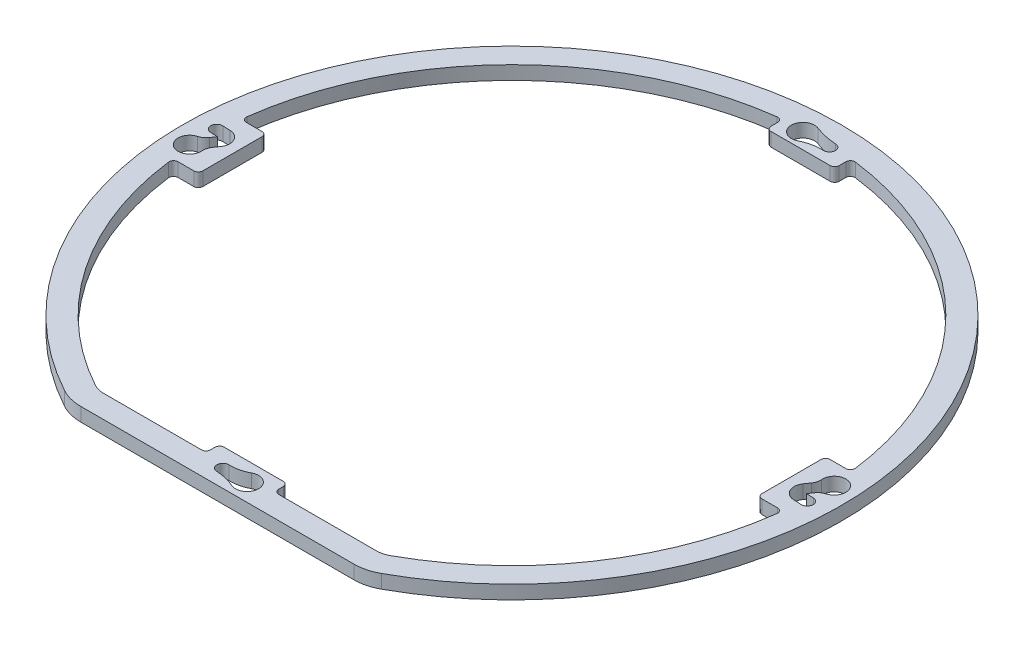
SolidWorks part; units mm, degrees
material "ABS"
ref_plane "Front Plane" through (0, 0, 0) normal (0, 0, 1) x (1, 0, 0)
ref_plane "Top Plane" through (0, 0, 0) normal (0, 1, 0) x (1, 0, 0)
ref_plane "Right Plane" through (0, 0, 0) normal (1, 0, 0) x (0, 0, -1)
sketch "Sketch1" plane through (0, 0, 0) normal (0, 1, 0) x (1, 0, 0)
  line L0 (-30.03, -64.8129) -> (30.03, -64.8129)
  line L1 (0, -85) -> (0, 0) construction
  line L2 (0, -85) -> (32.4891, -64.8129) construction
  line L3 (-30.03, -59.8129) -> (30.03, -59.8129)
  arc A0 (34.8348, -63.5829) -> (-34.8348, -63.5829) centre (0, 0) ccw
  circle A1 centre (0, -85) radius 38.25 construction
  arc A2 (30.03, -64.8129) -> (34.8348, -63.5829) centre (30.03, -54.8129) ccw
  arc A3 (-30.03, -64.8129) -> (-34.8348, -63.5829) centre (-30.03, -54.8129) cw
  arc A4 (32.4324, -59.1979) -> (-32.4324, -59.1979) centre (0, 0) ccw
  arc A5 (-30.03, -59.8129) -> (-32.4324, -59.1979) centre (-30.03, -54.8129) cw
  arc A6 (30.03, -59.8129) -> (32.4324, -59.1979) centre (30.03, -54.8129) ccw
  dimension "D1" = 145
  dimension "D2" = 76.5
  dimension "D4" = 10
  dimension "D3" = 85
  dimension "D5" = 5
extrude "Boss-Extrude1" add sketch "Sketch1" along normal blind 3
sketch "Sketch2" plane through (0, 3, 0) normal (0, 1, 0) x (1, 0, 0)
  line L0 (-30.03, -59.8129) -> (30.03, -59.8129) construction
  line L1 (7.5, -59.8129) -> (-7.5, -59.8129)
  line L2 (7.5, -59.8129) -> (7.5, -56.8129)
  line L3 (7.5, -56.8129) -> (-7.5, -56.8129)
  line L4 (-7.5, -59.8129) -> (-7.5, -56.8129)
  line L5 (-30.03, -64.8129) -> (30.03, -64.8129) construction
  line L6 (-61.5, -7.5) -> (-67.5, -7.5)
  line L7 (-61.5, -7.5) -> (-61.5, 7.5)
  line L8 (-61.5, 7.5) -> (-67.5, 7.5)
  line L9 (-67.5, -7.5) -> (-67.5, 7.5)
  line L10 (61.5, -7.5) -> (67.5, -7.5)
  line L11 (61.5, -7.5) -> (61.5, 7.5)
  line L12 (61.5, 7.5) -> (67.5, 7.5)
  line L13 (67.5, -7.5) -> (67.5, 7.5)
  line L14 (7.5, 67.5) -> (-7.5, 67.5)
  line L15 (7.5, 67.5) -> (7.5, 63.5)
  line L16 (7.5, 63.5) -> (-7.5, 63.5)
  line L17 (-7.5, 67.5) -> (-7.5, 63.5)
  arc A0 (32.4324, -59.1979) -> (-32.4324, -59.1979) centre (0, 0) ccw construction
  point P17 (-67.5, 0)
  point P18 (67.5, 0)
  point P20 (0, -56.8129)
  point P26 (0, 67.5)
  dimension "D4" = 4
  dimension "D1" = 15
  dimension "D2" = 8
  dimension "D3" = 15
  dimension "D5" = 6
extrude "Boss-Extrude2" add sketch "Sketch2" against normal up to surface (3 mm away) up to face at (0, 0, 30.3285)
sketch "Sketch3" plane through (0, 3, 0) normal (0, 1, 0) x (1, 0, 0)
  line L0 (0, 0) -> (2.6608, -60.9419) construction
  line L1 (0, 0) -> (-2.6608, -60.9419) construction
  line L2 (0, 0) -> (0, -64.8129) construction
  line L3 (-30.03, -64.8129) -> (30.03, -64.8129) construction
  line L4 (0, 0) -> (0, 72.5) construction
  line L5 (0, 0) -> (2.9225, 66.9362) construction
  line L6 (0, 0) -> (-2.9225, 66.9362) construction
  arc A0 (1.6164, -63.2683) -> (1.438, -58.7042) centre (2.6608, -60.9419) ccw
  arc A1 (-2.6041, -59.6432) -> (-2.7175, -62.2407) centre (-2.6608, -60.9419) ccw
  arc A2 (-2.6041, -59.6432) -> (1.438, -58.7042) centre (-2.2671, -51.9241) ccw
  arc A3 (1.6164, -63.2683) -> (-2.7175, -62.2407) centre (-3.2341, -74.0728) ccw
  arc A4 (34.8348, -63.5829) -> (-34.8348, -63.5829) centre (0, 0) ccw construction
  arc A5 (2.8658, 65.6375) -> (2.9792, 68.235) centre (2.9225, 66.9362) ccw
  arc A6 (-1.9738, 69.3032) -> (-1.7885, 64.6522) centre (-2.9225, 66.9362) ccw
  arc A7 (-1.9738, 69.3032) -> (2.9792, 68.235) centre (3.6371, 83.3026) ccw
  arc A8 (2.8658, 65.6375) -> (-1.7885, 64.6522) centre (2.45, 56.1152) ccw
  point P23 (0, 0)
  dimension "D1" = 2.6
  dimension "D2" = 5.1
  dimension "D6" = 5.1
  dimension "D7" = 2.6
  dimension "D3" = 5
  dimension "D4" = 2.5
  dimension "D5" = 61
  dimension "D8" = 2.5
  dimension "D9" = 5
  dimension "D10" = 67
extrude "Cut-Extrude1" cut sketch "Sketch3" against normal through all
sketch "Sketch4" plane through (0, 3, 0) normal (0, 1, 0) x (1, 0, 0)
  line L0 (0, 0) -> (-72.5, 0) construction
  line L1 (0, 0) -> (-67.9353, -2.9661) construction
  line L2 (0, 0) -> (-67.9353, 2.9661) construction
  line L3 (-67.9353, -2.9661) -> (-63.9391, 2.7916) construction
  line L4 (-67.992, 1.6674) -> (-66.4106, 1.5983)
  line L5 (-67.1396, 0.548) -> (-66.4106, 1.5983)
  line L6 (-69.0443, -2.1964) -> (-65.0481, 3.5614) construction
  line L7 (-64.9215, -0.9914) -> (-64.1565, 0.1107)
  line L8 (-67.8786, 4.2649) -> (-66.1791, 4.1907)
  line L9 (67.992, -1.6674) -> (66.4106, -1.5983)
  line L10 (67.1396, -0.548) -> (66.4106, -1.5983)
  line L11 (64.9215, 0.9914) -> (64.1565, -0.1107)
  line L12 (67.8786, -4.2649) -> (66.1791, -4.1907)
  line L13 (0, 0) -> (72.5, 0) construction
  line L14 (0, 0) -> (67.9353, 2.9661) construction
  line L15 (0, 0) -> (67.9353, -2.9661) construction
  line L16 (67.9353, 2.9661) -> (63.9391, -2.7916) construction
  arc A0 (34.8348, -63.5829) -> (-34.8348, -63.5829) centre (0, 0) ccw construction
  arc A1 (-67.8786, 4.2649) -> (-67.992, 1.6674) centre (-67.9353, 2.9661) ccw
  arc A2 (-68.6262, -0.5115) -> (-65.3941, -2.7547) centre (-67.9353, -2.9661) ccw
  arc A3 (-66.1791, 4.1907) -> (-64.1565, 0.1107) centre (-66.2925, 1.5932) cw
  arc A4 (-67.1396, 0.548) -> (-68.6262, -0.5115) centre (-69.3577, 2.0875) cw
  arc A5 (-64.9215, -0.9914) -> (-65.3941, -2.7547) centre (-62.7033, -2.5309) ccw
  arc A6 (67.8786, -4.2649) -> (67.992, -1.6674) centre (67.9353, -2.9661) ccw
  arc A7 (68.6262, 0.5115) -> (65.3941, 2.7547) centre (67.9353, 2.9661) ccw
  arc A8 (66.1791, -4.1907) -> (64.1565, -0.1107) centre (66.2925, -1.5932) cw
  arc A9 (67.1396, -0.548) -> (68.6262, 0.5115) centre (69.3577, -2.0875) cw
  arc A10 (64.9215, 0.9914) -> (65.3941, 2.7547) centre (62.7033, 2.5309) ccw
  point P42 (0, 0)
  dimension "D5" = 5.1
  dimension "D6" = 2.6
  dimension "D9" = 2.7
  dimension "D1" = 68
  dimension "D2" = 5
  dimension "D3" = 2.5
  dimension "D4" = 4
  dimension "D7" = 1.35
  dimension "D8" = 1.35
  dimension "D10" = 2
extrude "Cut-Extrude2" cut sketch "Sketch4" against normal through all
fillet "Fillet1" radius 1 16 edges at (61.5, 1.5, -7.5) (67.082, 1.5, -7.5) (61.5, 1.5, 7.5) (67.082, 1.5, 7.5) (-7.5, 1.5, -63.5) (-7.5, 1.5, -67.082) (7.5, 1.5, -63.5) (7.5, 1.5, -67.082) (-67.082, 1.5, -7.5) (-61.5, 1.5, -7.5) (-61.5, 1.5, 7.5) (-67.082, 1.5, 7.5) (-7.5, 1.5, 59.8129) (-7.5, 1.5, 56.8129) (7.5, 1.5, 56.8129) (7.5, 1.5, 59.8129)
equation "\"smallPulleyTeeth\"= 30"
equation "\"largePulleyTeeth\"= 30"
equation "\"eighthThick\"= 3.0mm"
equation "\"sixteenthThick\" = 1.7mm"
equation "\"quarterThick\"=6.0mm"
equation "\"OD\" = 145mm"
equation "\"puckAngle\" = 60.5deg"
equation "\"puckDiam\" = 76.5mm"
equation "\"axlePress\" = 5.9mm"
equation "\"press\" = 0.2mm"
equation "\"wheelClear\" = 0.3mm"
equation "\"10-32clear\" = 4.8mm"
equation "\"6-32clear\" = 3.3mm"
equation "\"8-32clear\" = 4.0mm"
equation "\"4-40clear\" = 3.0mm"
equation "\"wheelHeight\" = 22mm"
equation "\"wheelWell\" = 65mm"
equation "\"D1@Sketch1\"=\"OD\""
equation "\"D1@Boss-Extrude1\"=\"eighthThick\""
equation "\"D2@Sketch1\"=\"puckDiam\""
equation "\"puckDist\" = 85mm"
equation "\"scoopFillet\" = 5mm"
equation "\"10-32tap\" = 4.45mm"
equation "\"ledSmall\" = 3.1mm"
equation "\"ledLarge\" = 4.2mm"
equation "\"ledLength\" = 4.2mm"
equation "\"D3@Sketch1\"=\"puckDist\""
